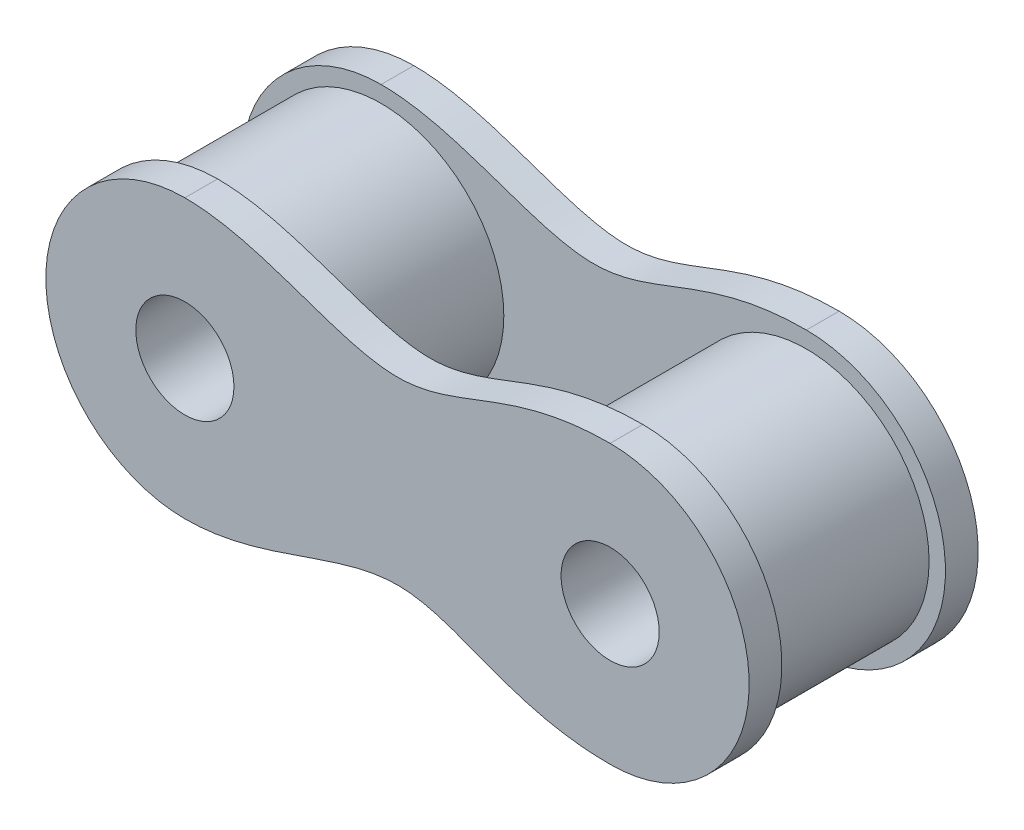
SolidWorks part; units mm, degrees
ref_plane "Front Plane" through (0, 0, 0) normal (0, 0, 1) x (1, 0, 0)
ref_plane "Top Plane" through (0, 0, 0) normal (0, 1, 0) x (1, 0, 0)
ref_plane "Right Plane" through (0, 0, 0) normal (1, 0, 0) x (0, 0, -1)
sketch "Sketch1" plane through (0, 0, 0) normal (0, 0, 1) x (1, 0, 0)
  circle A0 centre (0, 0) radius 1.5
  circle A1 centre (13, 0) radius 1.5
  circle A2 centre (0, 0) radius 3.75
  circle A3 centre (13, 0) radius 3.75
  dimension "D2" = 3
  dimension "D3" = 7.5
  dimension "D1" = 13
extrude "Boss-Extrude1" add sketch "Sketch1" along normal blind 5
sketch "Sketch2" plane through (0, 0, 5) normal (0, 0, 1) x (1, 0, 0)
  arc A0 (0, 4.25) -> (0, -4.25) centre (0, 0) ccw
  arc A1 (13, -4.25) -> (13, 4.25) centre (13, 0) ccw
  circle A2 centre (0, 0) radius 1.5
  circle A3 centre (13, 0) radius 1.5
  spline S0 degree 3 poles (0, 4.25) (2.3863, 4.25) (6.8636, 1.25) (9.8864, 4.25) (13, 4.25) knots 0 0 0 0 0.5 1 1 1 1
  spline S1 degree 3 poles (0, -4.25) (2.3863, -4.25) (6.8636, -1.25) (9.8864, -4.25) (13, -4.25) knots 0 0 0 0 0.5 1 1 1 1
  point P11 (6.5, 2.75)
  dimension "D1" = 8.5
  dimension "D2" = 3
extrude "Boss-Extrude2" add sketch "Sketch2" along normal blind 1
ref_plane "Plane1" through (0, 0, 2.5) normal (0, 0, -1) x (-1, 0, 0)
mirror "Mirror1" about plane through (0, 0, 2.5) normal (0, 0, -1) of "Boss-Extrude2"
